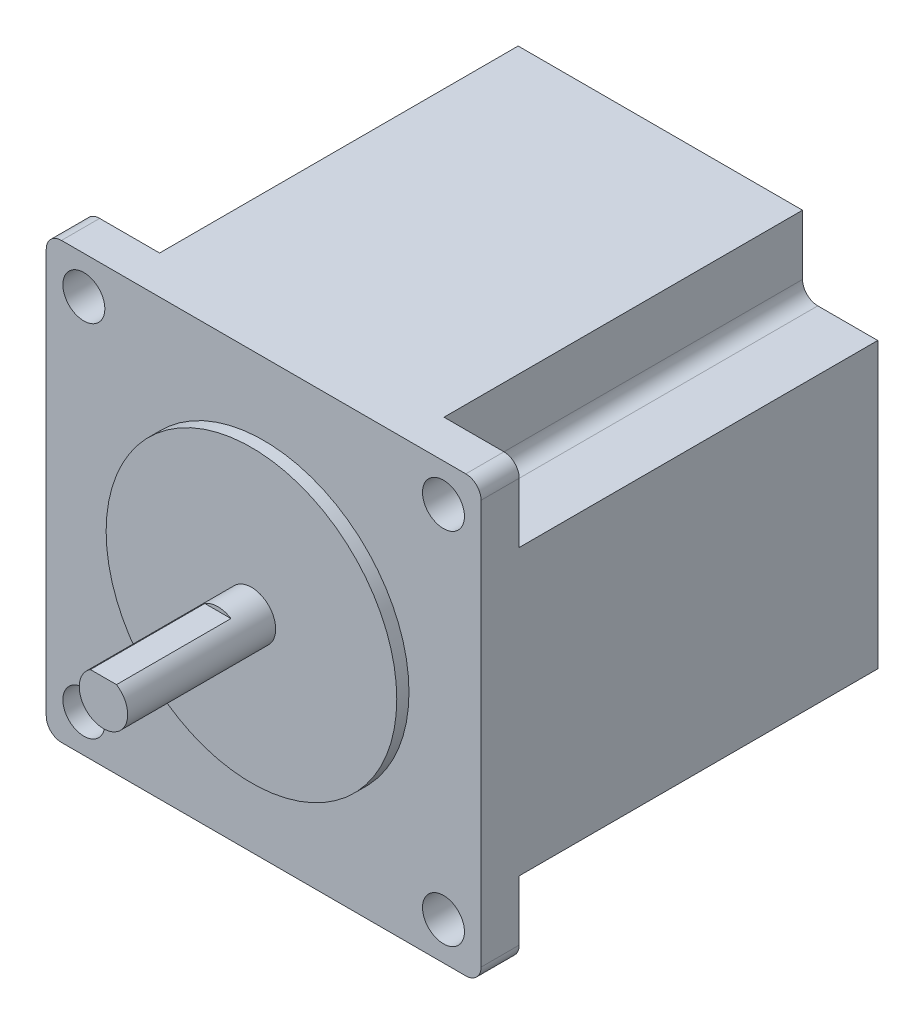
SolidWorks part; units mm, degrees
material "M2"
ref_plane "Front Plane" through (0, 0, 0) normal (0, 0, 1) x (1, 0, 0)
ref_plane "Top Plane" through (0, 0, 0) normal (0, 1, 0) x (1, 0, 0)
ref_plane "Right Plane" through (0, 0, 0) normal (1, 0, 0) x (0, 0, -1)
sketch "Sketch1" plane through (0, 0, 0) normal (0, 0, 1) x (1, 0, 0)
  line L1 (-28.5, -28.5) -> (28.5, -28.5)
  line L2 (-28.5, -28.5) -> (-28.5, 28.5)
  line L3 (-28.5, 28.5) -> (28.5, 28.5)
  line L4 (28.5, -28.5) -> (28.5, 28.5)
  line L5 (-28.5, -28.5) -> (28.5, 28.5) construction
  line L6 (-28.5, 28.5) -> (28.5, -28.5) construction
  point P0 (0, 0)
  dimension "D1" = 57
  dimension "D2" = 57
extrude "Boss-Extrude1" add sketch "Sketch1" along normal blind 52
sketch "Sketch2" plane through (0, 0, 52) normal (0, 0, 1) x (1, 0, 0)
  circle A0 centre (0, 0) radius 3.175
  dimension "D1" = 6.35
extrude "Boss-Extrude2" add sketch "Sketch2" along normal blind 21
fillet "Fillet1" radius 2 4 edges at (-28.5, -28.5, 26) (-28.5, 28.5, 26) (28.5, -28.5, 26) (28.5, 28.5, 26)
ref_plane "Plane1" through (0, 0, 46) normal (0, 0, 1) x (1, 0, 0)
sketch "Sketch9" plane through (0, 0, 52) normal (0, 0, 1) x (1, 0, 0)
  circle A0 centre (0, 0) radius 19.05
  dimension "D1" = 38.1
extrude "Boss-Extrude3" add sketch "Sketch9" along normal blind 1.6
sketch "Sketch11" plane through (0, 0, 52) normal (0, 0, 1) x (1, 0, 0)
  line L1 (-23.57, -23.57) -> (23.57, -23.57) construction
  line L2 (-23.57, -23.57) -> (-23.57, 23.57) construction
  line L3 (-23.57, 23.57) -> (23.57, 23.57) construction
  line L4 (23.57, -23.57) -> (23.57, 23.57) construction
  line L5 (-23.57, -23.57) -> (23.57, 23.57) construction
  line L6 (-23.57, 23.57) -> (23.57, -23.57) construction
  circle A0 centre (23.57, 23.57) radius 2.75
  circle A1 centre (23.57, -23.57) radius 2.75
  circle A2 centre (-23.57, -23.57) radius 2.75
  circle A3 centre (-23.57, 23.57) radius 2.75
  point P0 (0, 0)
  point P16 (0, 0)
  dimension "D2" = 5.5
  dimension "D1" = 47.14
  dimension "D3" = 4
extrude "Cut-Extrude3" cut sketch "Sketch11" against normal through all
sketch "Sketch10" plane through (0, 0, 73) normal (0, 0, 1) x (1, 0, 0)
  line L0 (-1.7103, 2.675) -> (1.7103, 2.675)
  circle A1 centre (0, 0) radius 3.175
  arc A2 (1.7103, 2.675) -> (-1.7103, 2.675) centre (0, 0) ccw
  dimension "D2" = 2.675
  dimension "D1" = 0
extrude "Cut-Extrude2" cut sketch "Sketch10" against normal blind 15
sketch "Sketch12" plane through (0, 0, 0) normal (0, 0, -1) x (-1, 0, 0)
  line L0 (-26.5, 28.5) -> (26.5, 28.5) construction
  line L1 (-28.5, 18.64) -> (-18.64, 18.64)
  line L2 (-28.5, 18.64) -> (-28.5, 28.5)
  line L3 (-28.5, 28.5) -> (-18.64, 28.5)
  line L4 (-18.64, 18.64) -> (-18.64, 28.5)
  line L5 (-28.5, 18.64) -> (-18.64, 28.5) construction
  line L6 (-28.5, 28.5) -> (-18.64, 18.64) construction
  point P0 (-23.57, 23.57)
extrude "Cut-Extrude4" cut sketch "Sketch12" against normal offset from surface (47 mm away) 5 up to face at (-20.82, 23.57, 52)
fillet "Fillet2" radius 2 1 edges at (18.64, 18.64, 23.5)
pattern_circular "CirPattern1" count 4 over 360 about axis through (0, 0, 0) along (0, 0, 1) of "Fillet2", "Cut-Extrude4"
equation "\"D2@Sketch10\"=6.35/2-6.35+5.85"
